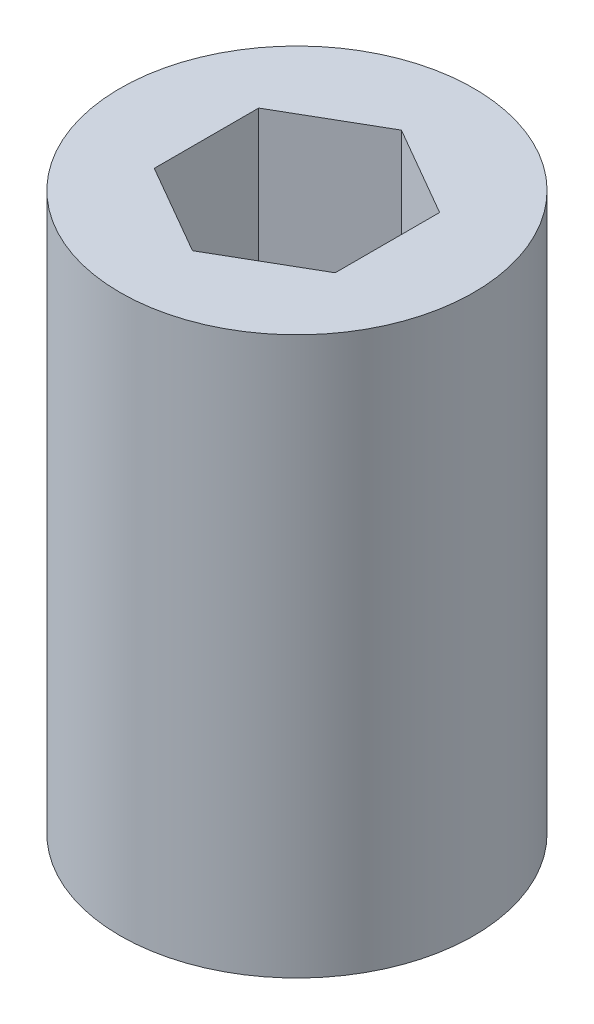
SolidWorks part; units mm, degrees
ref_plane "Front Plane" through (0, 0, 0) normal (0, 0, 1) x (1, 0, 0)
ref_plane "Top Plane" through (0, 0, 0) normal (0, 1, 0) x (1, 0, 0)
ref_plane "Right Plane" through (0, 0, 0) normal (1, 0, 0) x (0, 0, -1)
sketch "Sketch1" plane through (0, 0, 0) normal (0, 1, 0) x (1, 0, 0)
  line L1 (0, 15) -> (-12.9904, 7.5)
  line L2 (-12.9904, 7.5) -> (-12.9904, -7.5)
  line L3 (-12.9904, -7.5) -> (0, -15)
  line L4 (0, -15) -> (12.9904, -7.5)
  line L5 (12.9904, -7.5) -> (12.9904, 7.5)
  line L6 (12.9904, 7.5) -> (0, 15)
  circle A0 centre (0, 0) radius 25.4
  circle A1 centre (0, 0) radius 25.4
  circle A2 centre (0, 0) radius 12.9904 construction
  dimension "D1" = 50.8
  dimension "D2" = 50.8
  dimension "D3" = 15
extrude "Boss-Extrude1" add sketch "Sketch1" against normal blind 80 contours A1 L6 L5 L4 L3 L2 L1
